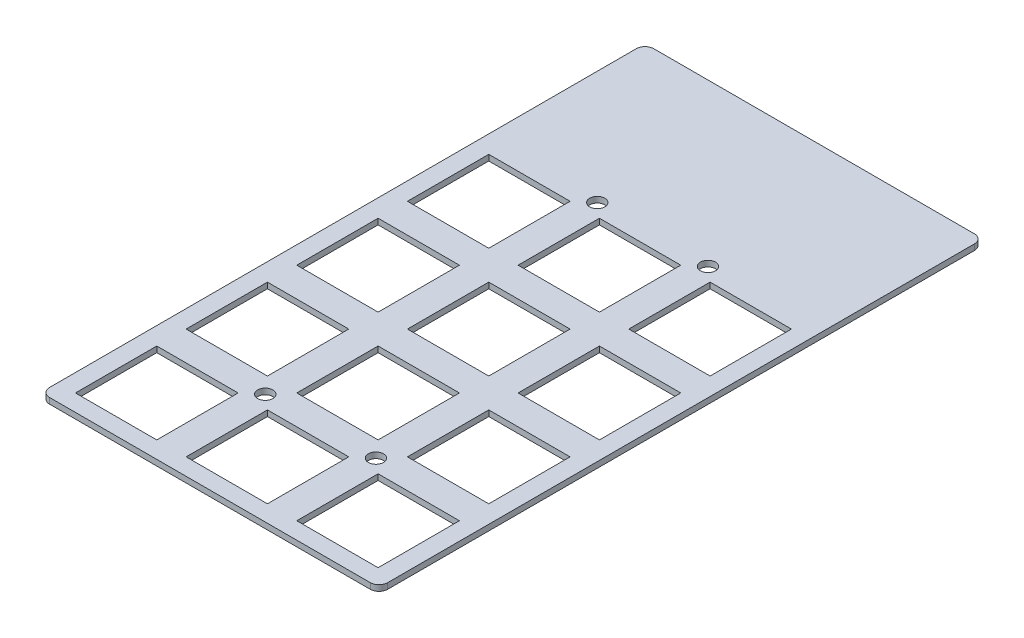
SolidWorks part; units mm, degrees
ref_plane "Front Plane" through (0, 0, 0) normal (0, 0, 1) x (1, 0, 0)
ref_plane "Top Plane" through (0, 0, 0) normal (0, 1, 0) x (1, 0, 0)
ref_plane "Right Plane" through (0, 0, 0) normal (1, 0, 0) x (0, 0, -1)
sketch "Sketch1" plane through (0, 0, 0) normal (0, 1, 0) x (1, 0, 0)
  line L1 (27.6, 52) -> (-27.6, 52)
  line L2 (29.1, 50.5) -> (29.1, -50.5)
  line L3 (27.6, -52) -> (-27.6, -52)
  line L4 (-29.1, 50.5) -> (-29.1, -50.5)
  line L5 (29.1, 52) -> (-29.1, -52) construction
  line L6 (29.1, -52) -> (-29.1, 52) construction
  line L7 (-9.525, -32.95) -> (9.525, -32.95) construction
  line L8 (-9.525, -32.95) -> (-9.525, 24.2) construction
  line L9 (-9.525, 24.2) -> (9.525, 24.2) construction
  line L10 (9.525, -32.95) -> (9.525, 24.2) construction
  line L15 (-7, -35.1) -> (7, -35.1)
  line L16 (-7, -35.1) -> (-7, -49.1)
  line L17 (-7, -49.1) -> (7, -49.1)
  line L18 (7, -35.1) -> (7, -49.1)
  line L19 (-7, -35.1) -> (7, -49.1) construction
  line L20 (-7, -49.1) -> (7, -35.1) construction
  line L24 (12.05, -35.1) -> (12.05, -49.1)
  line L25 (12.05, -35.1) -> (26.05, -35.1)
  line L26 (26.05, -35.1) -> (26.05, -49.1)
  line L27 (12.05, -49.1) -> (26.05, -49.1)
  line L28 (-26.05, -35.1) -> (-26.05, -49.1)
  line L29 (-26.05, -35.1) -> (-12.05, -35.1)
  line L30 (-12.05, -35.1) -> (-12.05, -49.1)
  line L31 (-26.05, -49.1) -> (-12.05, -49.1)
  line L32 (-26.05, -16.05) -> (-26.05, -30.05)
  line L33 (-26.05, -30.05) -> (-12.05, -30.05)
  line L34 (-12.05, -16.05) -> (-12.05, -30.05)
  line L35 (-26.05, -16.05) -> (-12.05, -16.05)
  line L36 (-7, -16.05) -> (-7, -30.05)
  line L37 (-7, -16.05) -> (7, -16.05)
  line L38 (7, -16.05) -> (7, -30.05)
  line L39 (-7, -30.05) -> (7, -30.05)
  line L40 (12.05, -16.05) -> (12.05, -30.05)
  line L41 (12.05, -30.05) -> (26.05, -30.05)
  line L42 (26.05, -16.05) -> (26.05, -30.05)
  line L43 (12.05, -16.05) -> (26.05, -16.05)
  line L44 (-26.05, 3) -> (-26.05, -11)
  line L45 (-26.05, -11) -> (-12.05, -11)
  line L46 (-12.05, 3) -> (-12.05, -11)
  line L47 (-26.05, 3) -> (-12.05, 3)
  line L48 (-7, 3) -> (-7, -11)
  line L49 (-7, 3) -> (7, 3)
  line L50 (7, 3) -> (7, -11)
  line L51 (-7, -11) -> (7, -11)
  line L52 (12.05, 3) -> (12.05, -11)
  line L53 (12.05, -11) -> (26.05, -11)
  line L54 (26.05, 3) -> (26.05, -11)
  line L55 (12.05, 3) -> (26.05, 3)
  line L56 (-26.05, 22.05) -> (-26.05, 8.05)
  line L57 (-26.05, 8.05) -> (-12.05, 8.05)
  line L58 (-12.05, 22.05) -> (-12.05, 8.05)
  line L59 (-26.05, 22.05) -> (-12.05, 22.05)
  line L60 (-7, 22.05) -> (-7, 8.05)
  line L61 (-7, 22.05) -> (7, 22.05)
  line L62 (7, 22.05) -> (7, 8.05)
  line L63 (-7, 8.05) -> (7, 8.05)
  line L64 (12.05, 22.05) -> (12.05, 8.05)
  line L65 (12.05, 8.05) -> (26.05, 8.05)
  line L66 (26.05, 22.05) -> (26.05, 8.05)
  line L67 (12.05, 22.05) -> (26.05, 22.05)
  line L68 (31.1, 51) -> (31.1, -51)
  line L69 (28.1, -54) -> (-28.1, -54)
  line L70 (-31.1, 51) -> (-31.1, -51)
  line L71 (28.1, 54) -> (-28.1, 54)
  line L72 (29.1, 52) -> (29.1, -52) construction
  line L73 (29.1, -52) -> (-29.1, -52) construction
  line L74 (-29.1, 52) -> (-29.1, -52) construction
  line L75 (29.1, 52) -> (-29.1, 52) construction
  line L76 (-31.1, 54) -> (-31.1, -54) construction
  line L77 (31.1, 54) -> (-31.1, 54) construction
  line L78 (31.1, 54) -> (31.1, -54) construction
  line L79 (31.1, -54) -> (-31.1, -54) construction
  circle A0 centre (-9.525, -32.95) radius 1.3
  circle A1 centre (9.525, -32.95) radius 1.3
  circle A2 centre (9.525, 24.2) radius 1.3
  circle A3 centre (-9.525, 24.2) radius 1.3
  arc A4 (29.1, -50.5) -> (27.6, -52) centre (27.6, -50.5) cw
  arc A5 (-27.6, -52) -> (-29.1, -50.5) centre (-27.6, -50.5) cw
  arc A6 (27.6, 52) -> (29.1, 50.5) centre (27.6, 50.5) cw
  arc A7 (-27.6, 52) -> (-29.1, 50.5) centre (-27.6, 50.5) ccw
  arc A8 (-31.1, 51) -> (-28.1, 54) centre (-28.1, 51) cw
  arc A9 (31.1, 51) -> (28.1, 54) centre (28.1, 51) ccw
  arc A10 (31.1, -51) -> (28.1, -54) centre (28.1, -51) cw
  arc A11 (-28.1, -54) -> (-31.1, -51) centre (-28.1, -51) cw
  point P0 (0, 0)
  point P10 (0, -42.1)
  dimension "D14" = 2.6
  dimension "D18" = 1.5
  dimension "D19" = 3
  dimension "D1" = 58.2
  dimension "D2" = 104
  dimension "D3" = 19.05
  dimension "D4" = 57.15
  dimension "D5" = 19.05
  dimension "D6" = 19.575
  dimension "D7" = 14
  dimension "D8" = 14
  dimension "D9" = 9.9
  dimension "D10" = 29.1
  dimension "D17" = 2
  dimension "D12" = 2
  dimension "D11" = 2
  dimension "D13" = 4
  dimension "D15" = 2
  dimension "D16" = 2
extrude "Boss-Extrude1" add sketch "Sketch1" along normal blind 1 contours L1 A7 L4 A5 L3 A4 L2 A6 L64 L67 L66 L65 L56 L59 L58 L57 L52 L55 L54 L53 L44 L47 L46 L45 L40 L43 L42 L41 L32 L35 L34 L33 L15 L18 L17 L16 L27 L24 L25 L26 L31 L28
